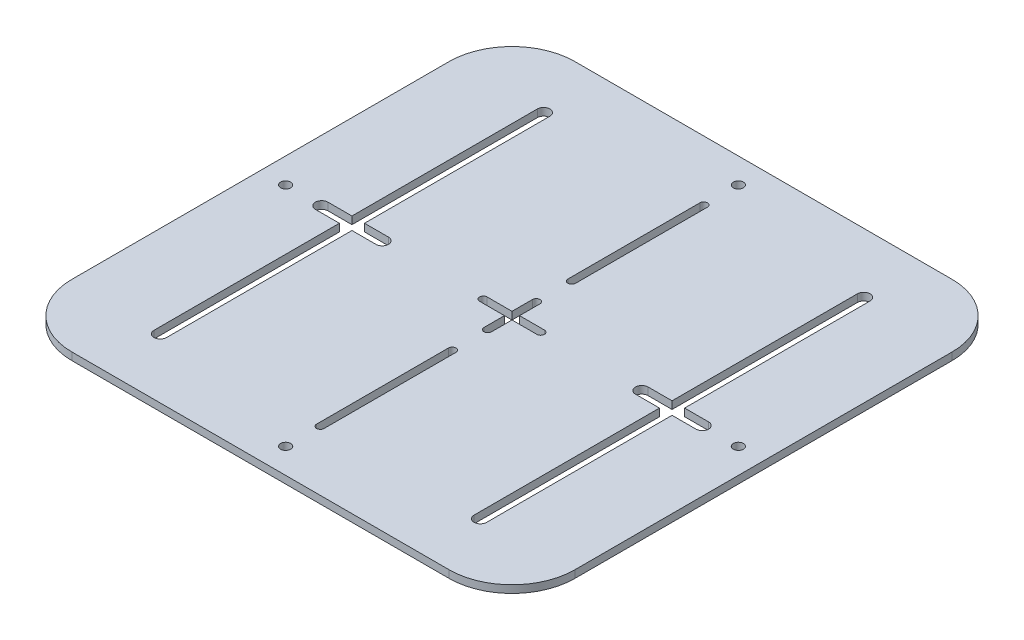
SolidWorks part; units mm, degrees
ref_plane "Спереди" through (0, 0, 0) normal (0, 0, 1) x (1, 0, 0)
ref_plane "Сверху" through (0, 0, 0) normal (0, 1, 0) x (1, 0, 0)
ref_plane "Справа" through (0, 0, 0) normal (1, 0, 0) x (0, 0, -1)
sketch "Эскиз1" plane through (0, 0, 0) normal (0, 1, 0) x (1, 0, 0)
  line L0 (-63.64, -76.2112) -> (-63.64, 76.2112) construction
  line L1 (-100, -100) -> (100, -100)
  line L2 (-100, -100) -> (-100, 100)
  line L3 (-100, 100) -> (100, 100)
  line L4 (100, -100) -> (100, 100)
  line L5 (0, 100) -> (0, -100) construction
  line L6 (-100, 0) -> (100, 0) construction
  line L7 (-66.14, -76.2112) -> (-66.14, 76.2112)
  line L8 (-61.14, -76.2112) -> (-61.14, 76.2112)
  line L9 (63.64, -76.2112) -> (63.64, 76.2112) construction
  line L10 (66.14, -76.2112) -> (66.14, 76.2112)
  line L11 (61.14, -76.2112) -> (61.14, 76.2112)
  line L12 (0, 76.2112) -> (0, 23.7473) construction
  line L13 (1.5, 76.2112) -> (1.5, 23.7473)
  line L14 (-1.5, 76.2112) -> (-1.5, 23.7473)
  line L15 (0, -76.2112) -> (0, -23.7473) construction
  line L16 (1.5, -76.2112) -> (1.5, -23.7473)
  line L17 (-1.5, -76.2112) -> (-1.5, -23.7473)
  line L18 (0, -9.6448) -> (0, 9.6448) construction
  line L19 (-1.5, -9.6448) -> (-1.5, 9.6448)
  line L20 (1.5, -9.6448) -> (1.5, 9.6448)
  arc A0 (-66.14, -76.2112) -> (-61.14, -76.2112) centre (-63.64, -76.2112) ccw
  arc A1 (-61.14, 76.2112) -> (-66.14, 76.2112) centre (-63.64, 76.2112) ccw
  arc A2 (66.14, -76.2112) -> (61.14, -76.2112) centre (63.64, -76.2112) cw
  arc A3 (61.14, 76.2112) -> (66.14, 76.2112) centre (63.64, 76.2112) cw
  circle A4 centre (-90, 0) radius 2
  circle A6 centre (0, 90) radius 2
  circle A7 centre (90, 0) radius 2
  circle A8 centre (0, -90) radius 2
  arc A9 (1.5, 76.2112) -> (-1.5, 76.2112) centre (0, 76.2112) ccw
  arc A10 (-1.5, 23.7473) -> (1.5, 23.7473) centre (0, 23.7473) ccw
  arc A11 (1.5, -76.2112) -> (-1.5, -76.2112) centre (0, -76.2112) cw
  arc A12 (-1.5, -23.7473) -> (1.5, -23.7473) centre (0, -23.7473) cw
  arc A13 (-1.5, -9.6448) -> (1.5, -9.6448) centre (0, -9.6448) ccw
  arc A14 (1.5, 9.6448) -> (-1.5, 9.6448) centre (0, 9.6448) ccw
  point P0 (0, 0)
  point P6 (-63.64, 0)
  point P13 (63.64, 0)
  point P22 (0, 49.9793)
  point P29 (0, 0)
  point P37 (0, -49.9793)
  point P42 (0, 0)
  dimension "D4" = 4
  dimension "D5" = 4
  dimension "D1" = 200
  dimension "D2" = 127.28
  dimension "D3" = 5
  dimension "D6" = 3
  dimension "D7" = 3
extrude "Бобышка-Вытянуть1" add sketch "Эскиз1" along normal blind 3
fillet "Скругление1" radius 25 4 edges at (-100, 1.5, 100) (-100, 1.5, -100) (100, 1.5, -100) (100, 1.5, 100)
sketch "Эскиз2" plane through (0, 3, 0) normal (0, 1, 0) x (1, 0, 0)
  line L0 (-113.9405, 0) -> (146.1512, 0) construction
  line L1 (63.64, 78.7112) -> (63.64, -78.7112) construction
  line L2 (51.6125, 0) -> (75.6675, 0) construction
  line L3 (51.6125, 2.5) -> (75.6675, 2.5)
  line L4 (51.6125, -2.5) -> (75.6675, -2.5)
  line L5 (0, 42.3135) -> (0, -38.8896) construction
  line L6 (-51.6125, 0) -> (-75.6675, 0) construction
  line L7 (-51.6125, 2.5) -> (-75.6675, 2.5)
  line L8 (-51.6125, -2.5) -> (-75.6675, -2.5)
  line L9 (-11.3961, 0) -> (11.3961, 0) construction
  line L10 (-11.3961, 1.5) -> (11.3961, 1.5)
  line L11 (-11.3961, -1.5) -> (11.3961, -1.5)
  arc A0 (66.14, 76.2112) -> (61.14, 76.2112) centre (63.64, 76.2112) ccw construction
  arc A1 (61.14, -76.2112) -> (66.14, -76.2112) centre (63.64, -76.2112) ccw construction
  arc A2 (51.6125, 2.5) -> (51.6125, -2.5) centre (51.6125, 0) ccw
  arc A3 (75.6675, -2.5) -> (75.6675, 2.5) centre (75.6675, 0) ccw
  arc A4 (-51.6125, 2.5) -> (-51.6125, -2.5) centre (-51.6125, 0) cw
  arc A5 (-75.6675, -2.5) -> (-75.6675, 2.5) centre (-75.6675, 0) cw
  arc A6 (-11.3961, 1.5) -> (-11.3961, -1.5) centre (-11.3961, 0) ccw
  arc A7 (11.3961, -1.5) -> (11.3961, 1.5) centre (11.3961, 0) ccw
  point P13 (63.64, 0)
  point P22 (-63.64, 0)
  point P29 (0, 0)
  dimension "D1" = 5
  dimension "D2" = 3
extrude "Вырез-Вытянуть1" cut sketch "Эскиз2" against normal blind 3
